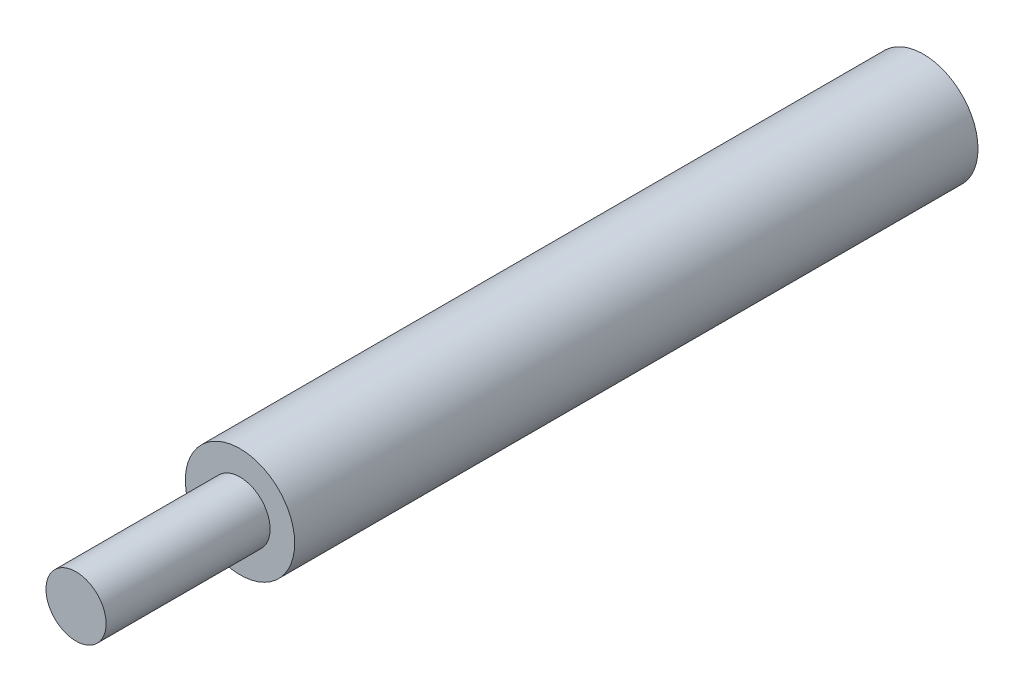
SolidWorks part; units mm, degrees
material "AISI 304"
ref_plane "Front Plane" through (0, 0, 0) normal (0, 0, 1) x (1, 0, 0)
ref_plane "Top Plane" through (0, 0, 0) normal (0, 1, 0) x (1, 0, 0)
ref_plane "Right Plane" through (0, 0, 0) normal (1, 0, 0) x (0, 0, -1)
sketch "Sketch1" plane through (0, 0, 0) normal (0, 0, 1) x (1, 0, 0)
  circle A0 centre (0, 0) radius 4
  dimension "D1" = 8
extrude "Boss-Extrude1" add sketch "Sketch1" along normal blind 50
sketch "Sketch2" plane through (0, 0, 50) normal (0, 0, 1) x (1, 0, 0)
  circle A0 centre (0, 0) radius 2.2
  dimension "D1" = 4.4
extrude "Boss-Extrude2" add sketch "Sketch2" along normal blind 12
sketch "Sketch3" plane through (0, 0, 0) normal (1, 0, 0) x (0, 0, -1)
  line L0 (-62, 2.2) -> (-62, 12.3828) construction
